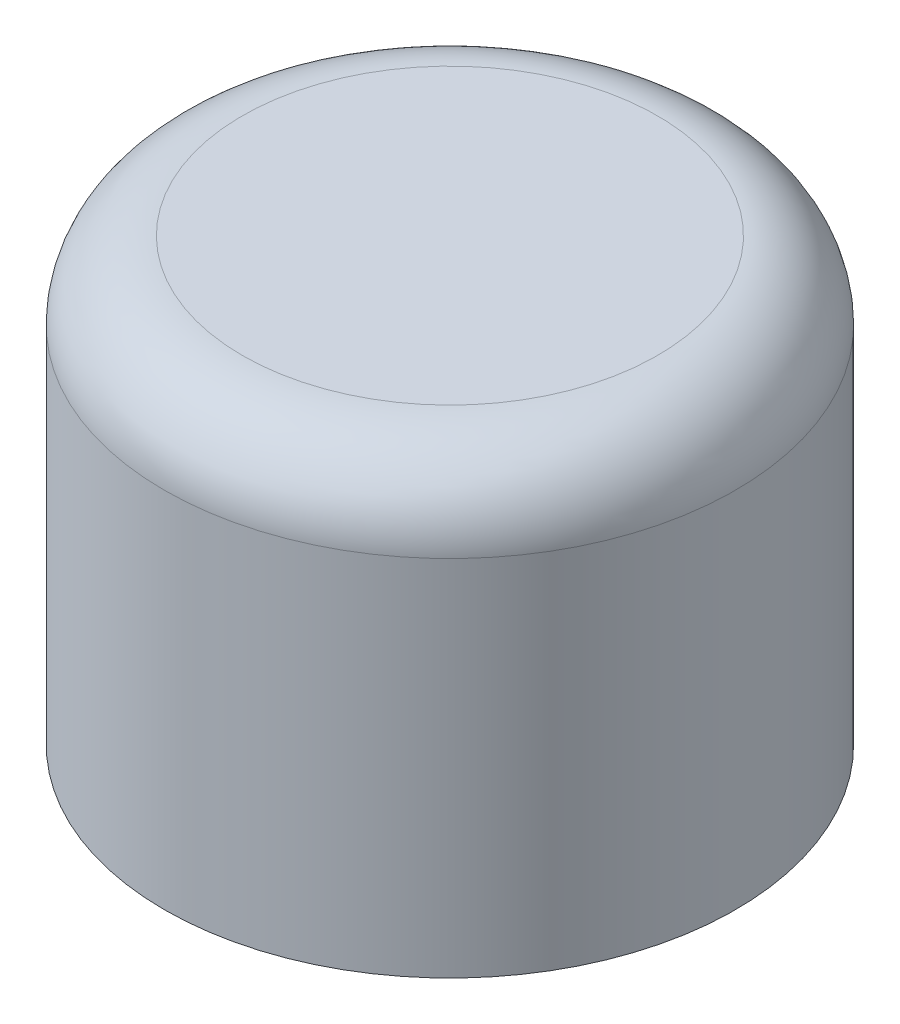
SolidWorks part; units mm, degrees
material "6061 Alloy"
ref_plane "Front Plane" through (0, 0, 0) normal (0, 0, 1) x (1, 0, 0)
ref_plane "Top Plane" through (0, 0, 0) normal (0, 1, 0) x (1, 0, 0)
ref_plane "Right Plane" through (0, 0, 0) normal (1, 0, 0) x (0, 0, -1)
sketch "Sketch1" plane through (0, 0, 0) normal (0, 1, 0) x (1, 0, 0)
  circle A0 centre (0, 0) radius 5.5
  dimension "D1" = 11
extrude "Boss-Extrude1" add sketch "Sketch1" along normal blind 8.5
fillet "Fillet1" radius 1.5 1 edges at (0, 8.5, 5.5)
shell "Shell1" thickness 2
